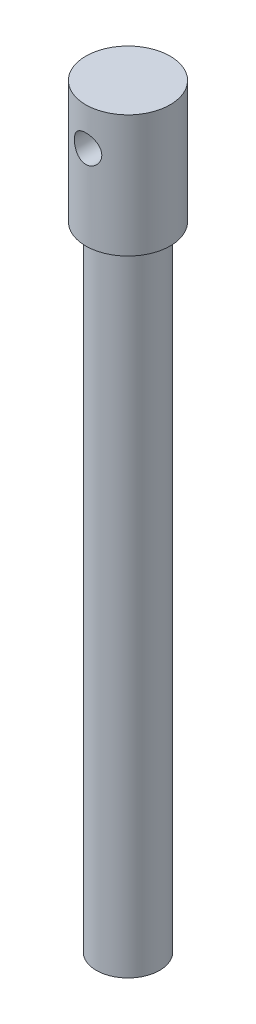
SolidWorks part; units mm, degrees
ref_plane "前视基准面" through (0, 0, 0) normal (0, 0, 1) x (1, 0, 0)
ref_plane "上视基准面" through (0, 0, 0) normal (0, 1, 0) x (1, 0, 0)
ref_plane "右视基准面" through (0, 0, 0) normal (1, 0, 0) x (0, 0, -1)
sketch "草图1" plane through (0, 0, 0) normal (0, 1, 0) x (1, 0, 0)
  circle A0 centre (0, 0) radius 7.5
  dimension "D1" = 15
extrude "凸台-拉伸1" add sketch "草图1" along normal blind 150
sketch "草图2" plane through (0, 150, 0) normal (0, 1, 0) x (1, 0, 0)
  circle A0 centre (0, 0) radius 10
  dimension "D1" = 20
extrude "凸台-拉伸2" add sketch "草图2" along normal blind 29
sketch "草图3" plane through (0, 0, 0) normal (0, 0, 1) x (1, 0, 0)
  circle A0 centre (0, 170) radius 3.25
  dimension "D1" = 6.5
  dimension "D2" = 9
extrude "切除-拉伸1" cut sketch "草图3" against normal through all both and the other way through all
